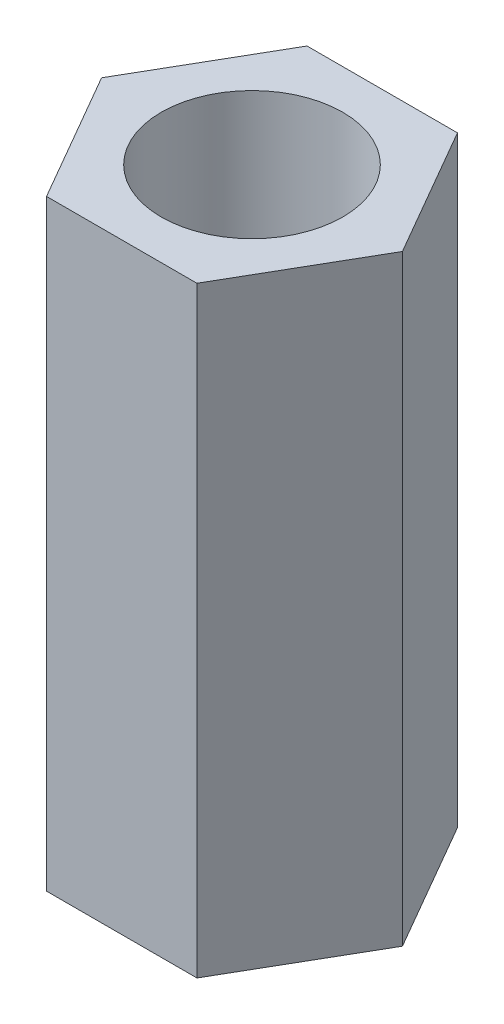
SolidWorks part; units mm, degrees
ref_plane "Plan de face" through (0, 0, 0) normal (0, 0, 1) x (1, 0, 0)
ref_plane "Plan de dessus" through (0, 0, 0) normal (0, 1, 0) x (1, 0, 0)
ref_plane "Plan de droite" through (0, 0, 0) normal (1, 0, 0) x (0, 0, -1)
sketch "Esquisse1" plane through (0, 0, 0) normal (0, 1, 0) x (1, 0, 0)
  line L1 (-7.25, 0) -> (-3.625, -6.2787)
  line L2 (-3.625, -6.2787) -> (3.625, -6.2787)
  line L3 (3.625, -6.2787) -> (7.25, 0)
  line L4 (7.25, 0) -> (3.625, 6.2787)
  line L5 (3.625, 6.2787) -> (-3.625, 6.2787)
  line L6 (-3.625, 6.2787) -> (-7.25, 0)
  dimension "D1" = 14.5
extrude "Boss.-Extru.1" add sketch "Esquisse1" along normal blind 29
sketch "Esquisse2" plane through (0, 0, 0) normal (0, -1, 0) x (1, 0, 0)
  circle A0 centre (0, 0) radius 4.375
  dimension "D1" = 8.75
extrude "Enlèv. mat.-Extru.1" cut sketch "Esquisse2" against normal blind 29
